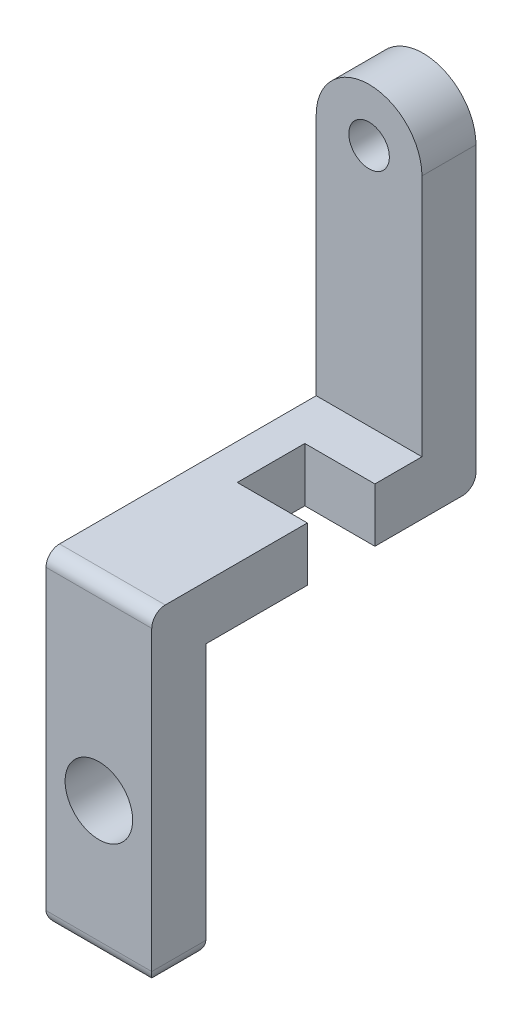
SolidWorks part; units mm, degrees
ref_plane "Přední rovina" through (0, 0, 0) normal (0, 0, 1) x (1, 0, 0)
ref_plane "Horní rovina" through (0, 0, 0) normal (0, 1, 0) x (1, 0, 0)
ref_plane "Pravá rovina" through (0, 0, 0) normal (1, 0, 0) x (0, 0, -1)
sketch "Skica1" plane through (0, 0, 0) normal (0, 0, 1) x (1, 0, 0)
  line L0 (108.4131, 104.5) -> (108.4131, 82.5)
  line L1 (117, 82.5) -> (-168, 82.5) construction
  line L2 (108.4131, 82.5) -> (100.5869, 82.5)
  line L3 (100.5869, 82.5) -> (100.5869, 104.5)
  circle A0 centre (104.5, 104.5) radius 1.5 construction
  circle A1 centre (104.5, 104.5) radius 1.5
  arc A2 (108.4131, 104.5) -> (100.5869, 104.5) centre (104.5, 104.5) ccw
extrude "Přidat vysunutím1" add sketch "Skica1" along normal blind 4
sketch "Skica2" plane through (0, 0, 4) normal (0, 0, 1) x (1, 0, 0)
  line L0 (100.5869, 104.5) -> (100.5869, 82.5) construction
  line L1 (108.4131, 82.5) -> (100.5869, 82.5)
  line L2 (108.4131, 82.5) -> (108.4131, 86.5)
  line L3 (108.4131, 86.5) -> (100.5869, 86.5)
  line L4 (100.5869, 82.5) -> (100.5869, 86.5)
  dimension "D1" = 4
extrude "Přidat vysunutím2" add sketch "Skica2" along normal up to surface (16 mm away)
sketch "Skica3" plane through (0, 0, 20) normal (0, 0, 1) x (1, 0, 0)
  line L0 (117, 62.5) -> (-168, 62.5) construction
  line L1 (100.5869, 86.5) -> (108.4131, 86.5)
  line L2 (100.5869, 86.5) -> (100.5869, 62.5)
  line L3 (100.5869, 62.5) -> (108.4131, 62.5)
  line L4 (108.4131, 86.5) -> (108.4131, 62.5)
  line L5 (108.4131, 86.5) -> (108.4131, 82.5) construction
  circle A0 centre (104.5, 72.5) radius 2.5
extrude "Přidat vysunutím3" add sketch "Skica3" along normal blind 4
sketch "Skica4" plane through (0, 86.5, 0) normal (0, 1, 0) x (1, 0, 0)
  line L0 (108.4131, -24) -> (108.4131, -4) construction
  line L1 (108.4131, -7.4822) -> (103.2249, -7.4822)
  line L2 (108.4131, -7.4822) -> (108.4131, -12.4822)
  line L3 (108.4131, -12.4822) -> (103.2249, -12.4822)
  line L4 (103.2249, -7.4822) -> (103.2249, -12.4822)
  dimension "D1" = 5
extrude "Odebrat vysunutím1" cut sketch "Skica4" against normal blind 4
fillet "Zaoblit1" radius 1 1 edges at (104.5, 86.5, 24)
fillet "Zaoblit2" radius 1 5 edges at (100.5869, 62.5, 22) (108.4131, 62.5, 22) (104.5, 62.5, 24) (104.5, 62.5, 20) (104.5, 82.5, 0)
